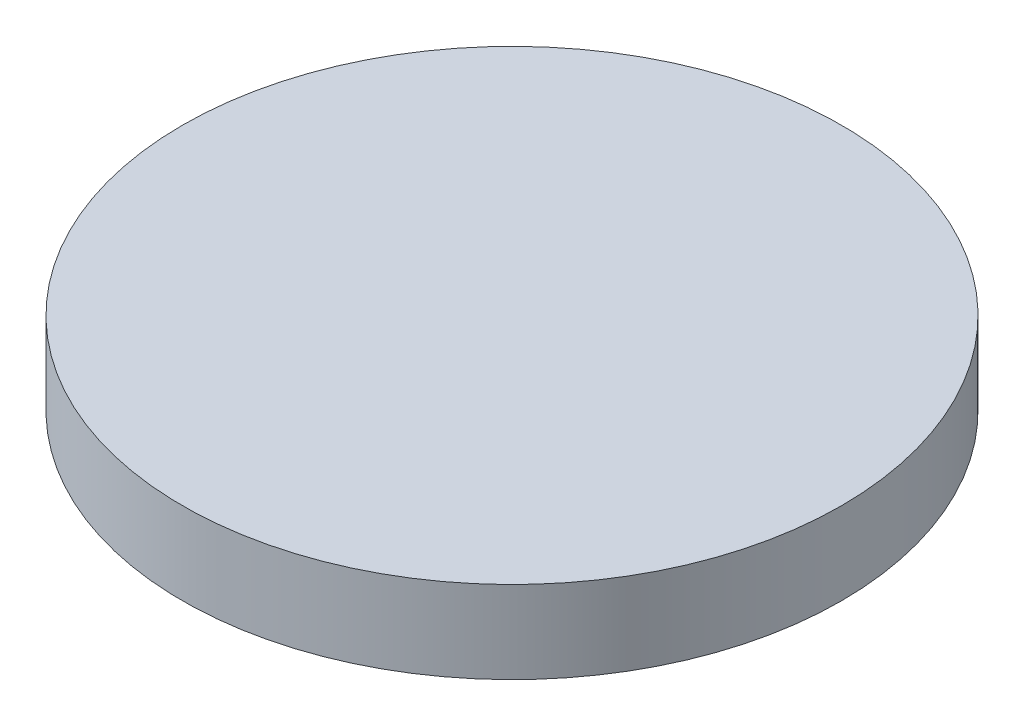
SolidWorks part; units mm, degrees
ref_plane "Front Plane" through (0, 0, 0) normal (0, 0, 1) x (1, 0, 0)
ref_plane "Top Plane" through (0, 0, 0) normal (0, 1, 0) x (1, 0, 0)
ref_plane "Right Plane" through (0, 0, 0) normal (1, 0, 0) x (0, 0, -1)
sketch "Sketch1" plane through (0, 0, 0) normal (0, 0, 1) x (1, 0, 0)
  line L1 (0, 0) -> (12.7, 0)
  line L2 (0, 0) -> (0, 3.175)
  line L3 (0, 3.175) -> (12.7, 3.175)
  line L4 (12.7, 0) -> (12.7, 3.175)
  point P5 (0, 1.5875)
  dimension "D1" = 12.7
  dimension "D2" = 3.175
revolve "Revolve1" add sketch "Sketch1" angle 360 about L2
